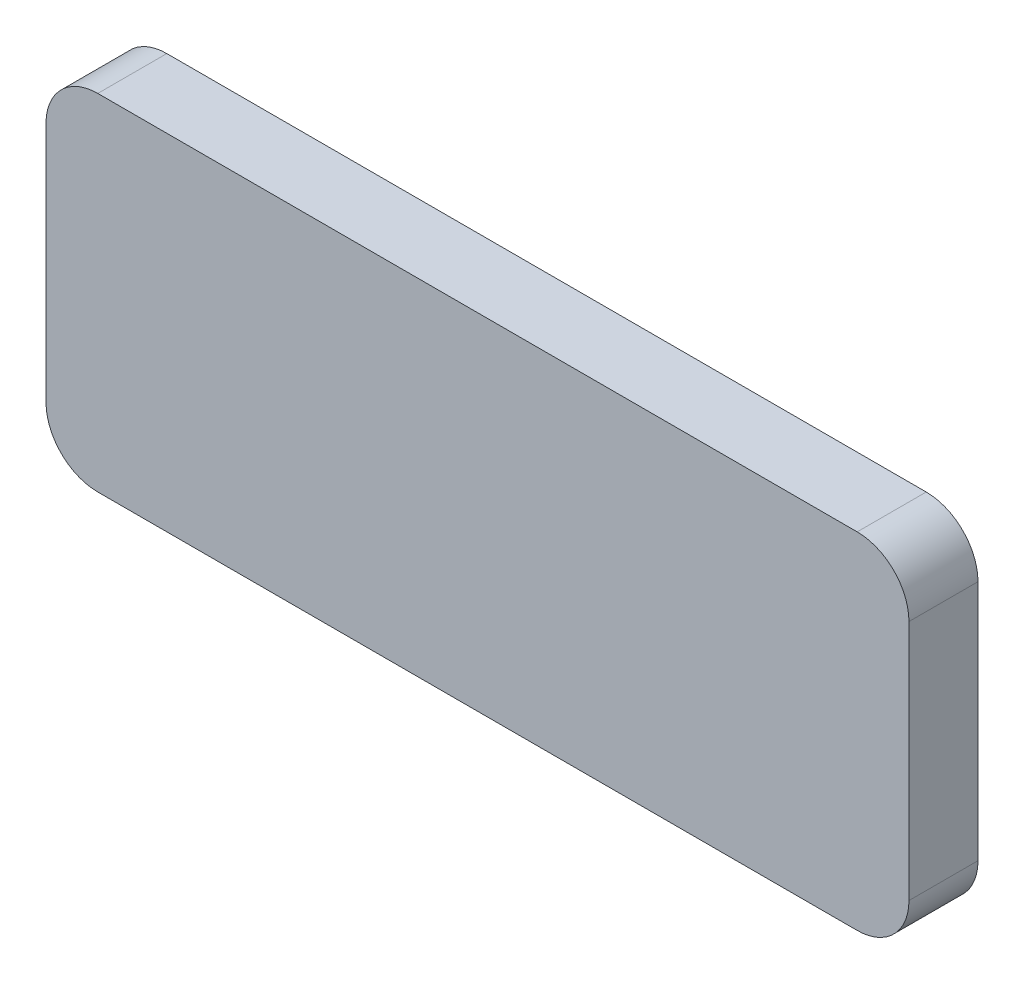
SolidWorks part; units mm, degrees
ref_plane "Front Plane" through (0, 0, 0) normal (0, 0, 1) x (1, 0, 0)
ref_plane "Top Plane" through (0, 0, 0) normal (0, 1, 0) x (1, 0, 0)
ref_plane "Right Plane" through (0, 0, 0) normal (1, 0, 0) x (0, 0, -1)
sketch "Sketch1" plane through (0, 0, 0) normal (0, 0, 1) x (1, 0, 0)
  line L0 (-0.2585, 48.4012) -> (-64.5181, 48.4012) construction
  line L1 (-22, 58.4012) -> (22, 58.4012)
  line L2 (-25, 55.4012) -> (-25, 41.4012)
  line L3 (-22, 38.4012) -> (22, 38.4012)
  line L4 (25, 55.4012) -> (25, 41.4012)
  line L6 (0, 0) -> (0, 22.2) construction
  arc A0 (22, 58.4012) -> (25, 55.4012) centre (22, 55.4012) cw
  arc A1 (22, 38.4012) -> (25, 41.4012) centre (22, 41.4012) ccw
  arc A2 (-25, 41.4012) -> (-22, 38.4012) centre (-22, 41.4012) ccw
  arc A3 (-22, 58.4012) -> (-25, 55.4012) centre (-22, 55.4012) ccw
  point P13 (25, 58.4012)
  point P16 (25, 38.4012)
  point P21 (-25, 58.4012)
  dimension "D5" = 3
  dimension "D1" = 10
  dimension "D2" = 20
  dimension "D3" = 50
  dimension "D4" = 25
extrude "Boss-Extrude1" add sketch "Sketch1" along normal blind 4
